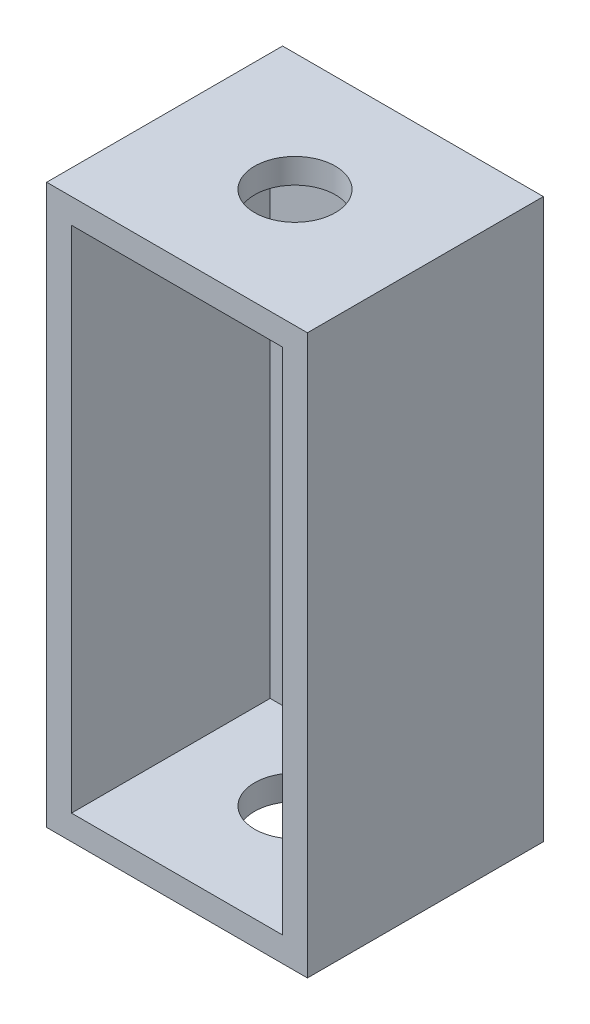
SolidWorks part; units mm, degrees
ref_plane "前视基准面" through (0, 0, 0) normal (0, 0, 1) x (1, 0, 0)
ref_plane "上视基准面" through (0, 0, 0) normal (0, 1, 0) x (1, 0, 0)
ref_plane "右视基准面" through (0, 0, 0) normal (1, 0, 0) x (0, 0, -1)
other "Configuration Table"
sketch "草图1" plane through (0, 0, 0) normal (0, 0, 1) x (1, 0, 0)
  line L0 (0, 0) -> (42, 0)
  line L1 (42, 0) -> (42, 90)
  line L2 (42, 90) -> (0, 90)
  line L3 (0, 90) -> (0, 0)
  dimension "width" = 42
  dimension "height" = 90
extrude "Housing_envelope" add sketch "草图1" along normal blind 38
sketch "草图2" plane through (0, 0, 38) normal (0, 0, 1) x (1, 0, 0)
  line L0 (4, 4) -> (38, 4)
  line L1 (38, 4) -> (38, 86)
  line L2 (38, 86) -> (4, 86)
  line L3 (4, 86) -> (4, 4)
  dimension "x0" = 4
  dimension "x1" = 38
  dimension "y0" = 4
  dimension "y2" = 86
extrude "Front_access_window" cut sketch "草图2" against normal blind 32
sketch "草图3" plane through (0, 90, 0) normal (0, 1, 0) x (1, 0, 0)
  circle A0 centre (21, -19) radius 6.5
  dimension "diameter" = 13
  dimension "x" = 21
  dimension "y" = 19
extrude "Axial_passage" cut sketch "草图3" against normal through all
